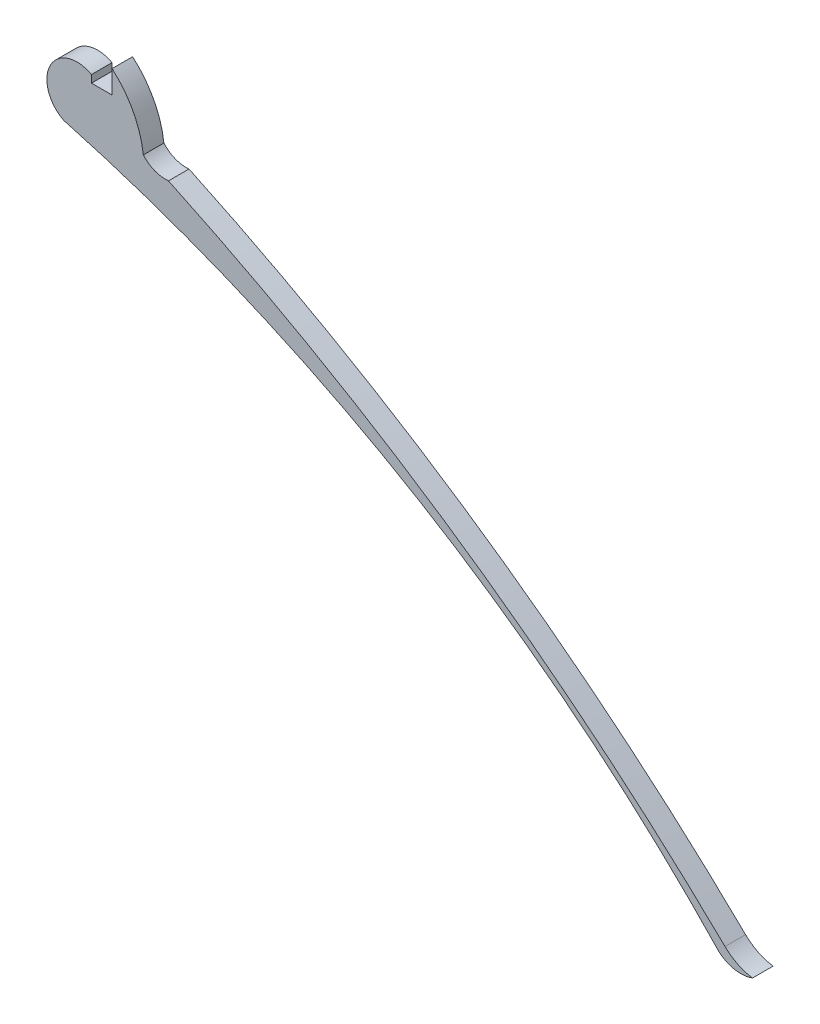
SolidWorks part; units mm, degrees
ref_plane "Front Plane" through (0, 0, 0) normal (0, 0, 1) x (1, 0, 0)
ref_plane "Top Plane" through (0, 0, 0) normal (0, 1, 0) x (1, 0, 0)
ref_plane "Right Plane" through (0, 0, 0) normal (1, 0, 0) x (0, 0, -1)
sketch "Sketch1" plane through (0, 0, 0) normal (0, 0, 1) x (1, 0, 0)
  line L0 (0, 30.2381) -> (-1.524, 30.2381)
  line L1 (-1.524, 30.2381) -> (-1.524, 30.7906)
  line L2 (0, 30.2381) -> (0, 31.9367)
  arc A0 (-1.524, 30.7906) -> (-3.5744, 26.8183) centre (-2.5924, 28.8267) ccw
  arc A1 (-3.5744, 26.8183) -> (45.0105, -2.2894) centre (-31.1448, -74.3023) cw
  arc A2 (0, 31.9367) -> (2.3185, 27.5547) centre (-4.5068, 26.7479) cw
  arc A3 (2.3185, 27.5547) -> (4.181, 26.8183) centre (3.9573, 28.9761) ccw
  arc A4 (4.181, 26.8183) -> (45.4278, -1.6991) centre (-59.6698, -109.622) cw
  arc A5 (45.0105, -2.2894) -> (47.468, -2.7003) centre (46.5948, -0.3683) ccw
  arc A6 (45.4278, -1.6991) -> (47.468, -2.7003) centre (47.9793, 0.921) ccw
extrude "Boss-Extrude1" add sketch "Sketch1" along normal blind 1.524
